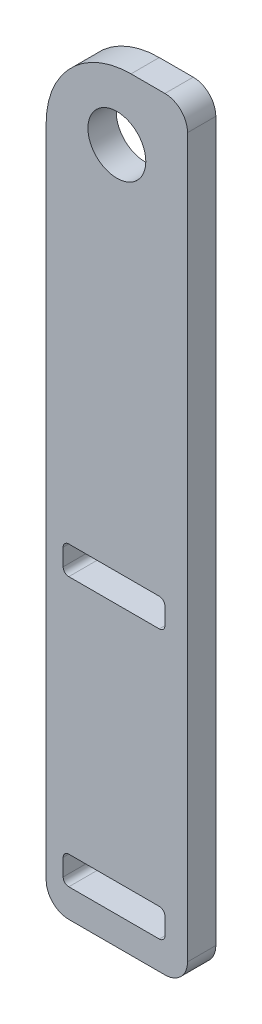
SolidWorks part; units mm, degrees
material "AISI 4130 Steel, annealed at 865C"
ref_plane "X-Y Datum" through (0, 0, 0) normal (0, 0, 1) x (1, 0, 0)
ref_plane "X-Z Datum" through (0, 0, 0) normal (0, 1, 0) x (1, 0, 0)
ref_plane "Y-Z Datum" through (0, 0, 0) normal (1, 0, 0) x (0, 0, -1)
sketch "Sketch1" plane through (0, 0, 0) normal (0, 0, 1) x (1, 0, 0)
  line L0 (-7.9375, -1.8309) -> (-7.9375, -75.4909)
  line L1 (-5.3975, -78.0309) -> (5.3975, -78.0309)
  line L2 (7.9375, -75.4909) -> (7.9375, 5.1541)
  line L3 (1.5875, 7.6941) -> (5.3975, 7.6941)
  line L5 (-5.3975, -71.6809) -> (4.7625, -71.6809)
  line L6 (-6.0325, -72.3159) -> (-6.0325, -74.2209)
  line L7 (-5.3975, -74.8559) -> (4.7625, -74.8559)
  line L8 (5.3975, -72.3159) -> (5.3975, -74.2209)
  line L14 (-0.3175, -71.6809) -> (-0.3175, -58.1872) construction
  line L15 (-0.3175, -58.1872) -> (4.7625, -58.1872) construction
  line L16 (-5.3975, -41.5184) -> (4.7625, -41.5184)
  line L17 (5.3975, -44.0584) -> (5.3975, -42.1534)
  line L18 (-5.3975, -44.6934) -> (4.7625, -44.6934)
  line L19 (-6.0325, -44.0584) -> (-6.0325, -42.1534)
  circle A0 centre (0, 0) radius 3.25
  circle A1 centre (0, 0) radius 7.5 construction
  arc A2 (-7.9375, -1.8309) -> (1.5875, 7.6941) centre (1.5875, -1.8309) cw
  arc A3 (7.9375, -75.4909) -> (5.3975, -78.0309) centre (5.3975, -75.4909) cw
  arc A4 (-5.3975, -78.0309) -> (-7.9375, -75.4909) centre (-5.3975, -75.4909) cw
  arc A5 (7.9375, 5.1541) -> (5.3975, 7.6941) centre (5.3975, 5.1541) ccw
  arc A6 (5.3975, -74.2209) -> (4.7625, -74.8559) centre (4.7625, -74.2209) cw
  arc A7 (5.3975, -72.3159) -> (4.7625, -71.6809) centre (4.7625, -72.3159) ccw
  arc A8 (-6.0325, -72.3159) -> (-5.3975, -71.6809) centre (-5.3975, -72.3159) cw
  arc A9 (-5.3975, -74.8559) -> (-6.0325, -74.2209) centre (-5.3975, -74.2209) cw
  arc A10 (5.3975, -42.1534) -> (4.7625, -41.5184) centre (4.7625, -42.1534) ccw
  arc A11 (5.3975, -44.0584) -> (4.7625, -44.6934) centre (4.7625, -44.0584) cw
  arc A12 (-6.0325, -44.0584) -> (-5.3975, -44.6934) centre (-5.3975, -44.0584) ccw
  arc A13 (-5.3975, -41.5184) -> (-6.0325, -42.1534) centre (-5.3975, -42.1534) ccw
  point P9 (0, -78.0309)
  point P30 (-6.0325, -71.6809)
  dimension "D1" = 15
  dimension "D2" = 6.5
  dimension "D6" = 9.525
  dimension "D7" = 2.54
  dimension "D9" = 0.635
  dimension "D3" = 15.875
  dimension "D5" = 7.6941
  dimension "D8" = 3.175
  dimension "D10" = 3.175
extrude "Boss-Extrude1" add sketch "Sketch1" along normal blind 3.175
